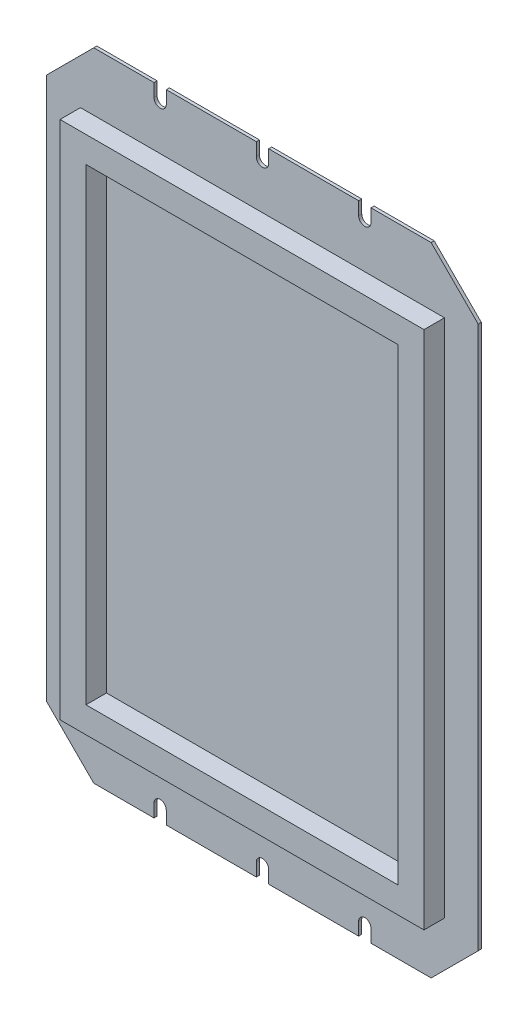
SolidWorks part; units mm, degrees
ref_plane "Front Plane" through (0, 0, 0) normal (0, 0, 1) x (1, 0, 0)
ref_plane "Top Plane" through (0, 0, 0) normal (0, 1, 0) x (1, 0, 0)
ref_plane "Right Plane" through (0, 0, 0) normal (1, 0, 0) x (0, 0, -1)
sketch "Sketch1" plane through (0, 0, 0) normal (0, 0, 1) x (1, 0, 0)
  line L0 (-105.41, 132.575) -> (-82.41, 155.575) construction
  line L1 (-105.41, -155.575) -> (105.41, -155.575)
  line L2 (-105.41, -155.575) -> (-105.41, 155.575)
  line L3 (-105.41, 155.575) -> (105.41, 155.575)
  line L4 (105.41, -155.575) -> (105.41, 155.575)
  line L5 (-105.41, -155.575) -> (105.41, 155.575) construction
  line L6 (-105.41, 155.575) -> (105.41, -155.575) construction
  line L8 (-50, -149.225) -> (50, -149.225) construction
  line L9 (-50, -149.225) -> (-50, 149.225) construction
  line L10 (-50, 149.225) -> (50, 149.225) construction
  line L11 (50, -149.225) -> (50, 149.225) construction
  line L12 (0, 149.225) -> (0, -149.225) construction
  line L13 (-50, 0) -> (50, 0) construction
  circle A0 centre (50, 149.225) radius 3
  point P0 (0, 0)
  point P8 (0, 0)
  point P13 (0, 149.225)
  point P14 (50, 152.225)
  dimension "Mounting Hole Diameter" = 6
  dimension "Height" = 311.15
  dimension "Width" = 210.82
  dimension "Chamfer Angle" = 45
  dimension "Chamfer Distance" = 23
  dimension "Mounting Hole Center to Center Height" = 298.45
  dimension "Mounting Hole Center to Center Width" = 100
  dimension "Mounting Hole Spacing" = 50
sketch "Sketch2" plane through (0, 0, 0) normal (1, 0, 0) x (0, 0, -1)
  line L0 (-0.75, 155.575) -> (0.75, 155.575) construction
  point P3 (0, 155.575)
  dimension "Thickness" = 1.5
sketch "Sketch3" plane through (0, 0, 0) normal (0, 0, 1) x (1, 0, 0)
  line L0 (-105.41, 132.575) -> (-82.41, 155.575)
  line L1 (-82.41, 155.575) -> (82.41, 155.575)
  line L2 (-105.41, 155.575) -> (105.41, 155.575) construction
  line L3 (82.41, 155.575) -> (105.41, 132.575)
  line L4 (105.41, -155.575) -> (105.41, 155.575) construction
  line L5 (105.41, 132.575) -> (105.41, -132.575)
  line L6 (105.41, -132.575) -> (82.41, -155.575)
  line L7 (-105.41, -155.575) -> (105.41, -155.575) construction
  line L8 (82.41, -155.575) -> (-82.41, -155.575)
  line L9 (-82.41, -155.575) -> (-105.41, -132.575)
  line L10 (-105.41, -155.575) -> (-105.41, 155.575) construction
  line L11 (-105.41, -132.575) -> (-105.41, 132.575)
extrude "Boss-Extrude1" add sketch "Sketch3" against normal up to vertex (0.75 mm away) and the other way up to vertex (0.75 mm away) up to point (0, 155.575, -0.75) other way up to point (0, 155.575, 0.75)
sketch "Sketch4" plane through (0, 0, 0) normal (0, 0, 1) x (1, 0, 0)
  line L1 (53, 149.225) -> (53, 155.575)
  line L3 (-105.41, 155.575) -> (105.41, 155.575) construction
  line L6 (53, 155.575) -> (47, 155.575)
  line L7 (47, 155.575) -> (47, 149.225)
  circle A0 centre (50, 149.225) radius 3 construction
  arc A1 (47, 149.225) -> (53, 149.225) centre (50, 149.225) ccw
extrude "Cut-Extrude1" cut sketch "Sketch4" against normal through all both and the other way through all
pattern_linear "LPattern1" count 7 spacing 50 along (-1, 0, 0) of "Cut-Extrude1"
mirror "Mirror1" about plane through (0, 0, 0) normal (0, 1, 0) of "Cut-Extrude1", "LPattern1"
sketch "Sketch6" plane through (0, 0, -0.75) normal (0, 0, -1) x (-1, 0, 0)
  line L1 (-88.9, 127) -> (88.9, 127)
  line L2 (-88.9, 127) -> (-88.9, -127)
  line L3 (-88.9, -127) -> (88.9, -127)
  line L4 (88.9, 127) -> (88.9, -127)
  line L5 (-88.9, 127) -> (88.9, -127) construction
  line L6 (-88.9, -127) -> (88.9, 127) construction
  line L7 (-76.2, 114.3) -> (76.2, 114.3)
  line L8 (-76.2, 114.3) -> (-76.2, -114.3)
  line L9 (-76.2, -114.3) -> (76.2, -114.3)
  line L10 (76.2, 114.3) -> (76.2, -114.3)
  line L11 (-76.2, 114.3) -> (76.2, -114.3) construction
  line L12 (-76.2, -114.3) -> (76.2, 114.3) construction
  point P0 (0, 0)
  point P6 (0, 0)
  dimension "D1" = 177.8
  dimension "D2" = 12.7
  dimension "D3" = 12.7
  dimension "D4" = 254
extrude "Boss-Extrude2" add sketch "Sketch6" against normal blind 11.5
equation "\"D3@LPattern1\"=\"Mounting Hole Spacing@Sketch1\""
equation "\"D1@LPattern1\"=(\"Mounting Hole Center to Center Height@Sketch1\"/\"Mounting Hole Spacing@Sketch1\")+1"
